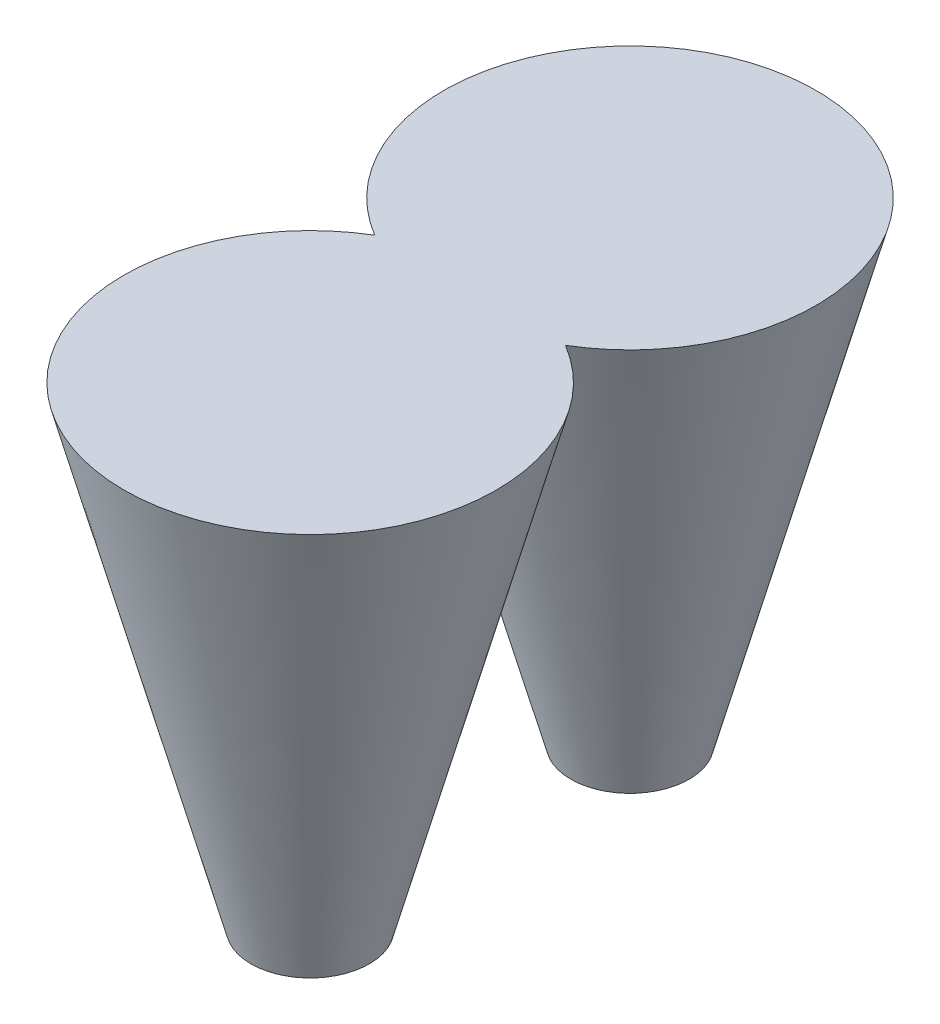
SolidWorks part; units mm, degrees
ref_plane "Plano frontal" through (0, 0, 0) normal (0, 0, 1) x (1, 0, 0)
ref_plane "Plano superior" through (0, 0, 0) normal (0, 1, 0) x (1, 0, 0)
ref_plane "Plano direito" through (0, 0, 0) normal (1, 0, 0) x (0, 0, -1)
sketch "Esboço1" plane through (0, 0, 0) normal (0, 1, 0) x (1, 0, 0)
  line L0 (1500, -1750) -> (1500, 1750) construction
  line L1 (1500, 1750) -> (-1500, 1750) construction
  line L2 (-1500, 1750) -> (-1500, -1750) construction
  line L3 (-1500, -1750) -> (1500, -1750) construction
  line L4 (0, 1750) -> (0, -1750) construction
  circle A1 centre (-4000, -550) radius 500
  circle A2 centre (-4000, 2150) radius 500
  point P2 (0, 0)
  dimension "D1" = 1000
  dimension "D2" = 1000
  dimension "D3" = 2500
  dimension "D4" = 2500
  dimension "D5" = 1200
  dimension "D6" = 400
extrude "Ressalto-extrusão1" add sketch "Esboço1" along normal blind 4000 draft 15 contours A1 | A2
